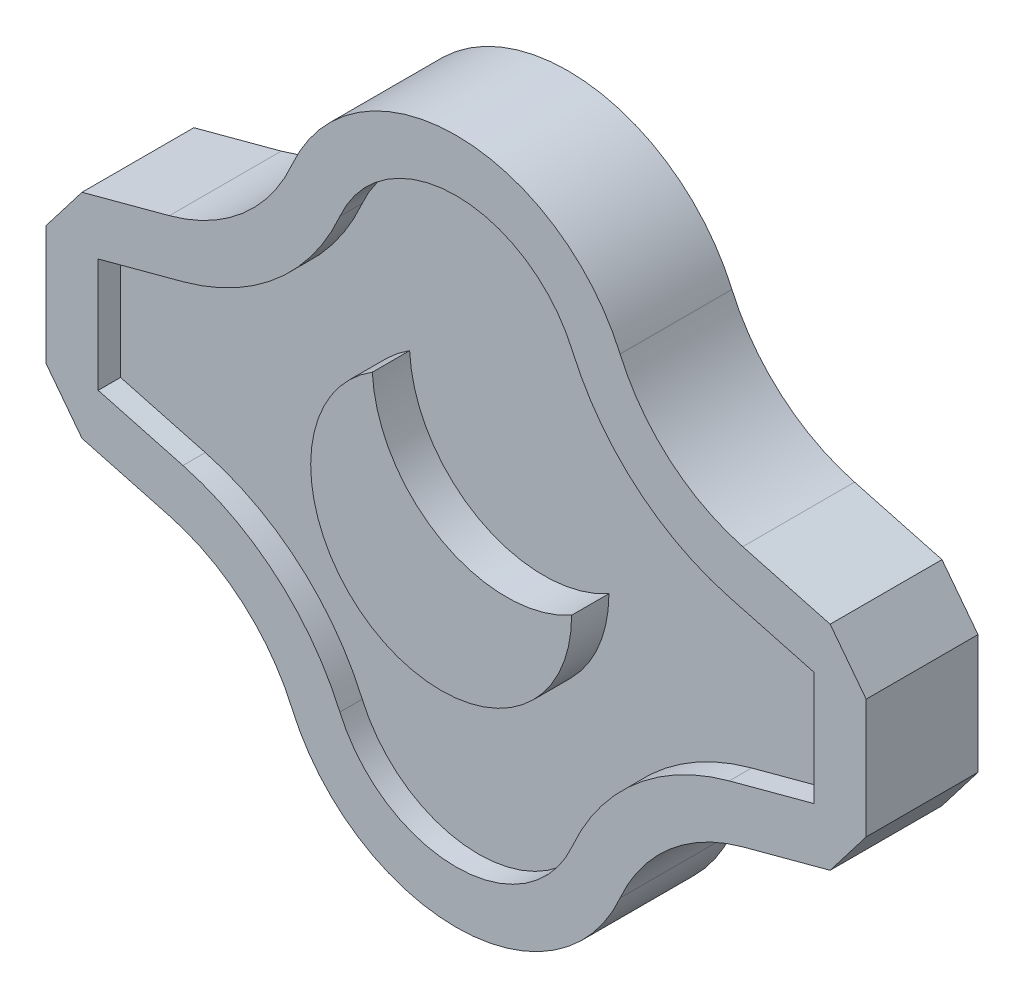
SolidWorks part; units mm, degrees
ref_plane "Front Plane" through (0, 0, 0) normal (0, 0, 1) x (1, 0, 0)
ref_plane "Top Plane" through (0, 0, 0) normal (0, 1, 0) x (1, 0, 0)
ref_plane "Right Plane" through (0, 0, 0) normal (1, 0, 0) x (0, 0, -1)
sketch "Sketch1" plane through (0, 0, 0) normal (0, 0, 1) x (1, 0, 0)
  line L0 (0, 0) -> (-65.8922, 0) construction
  line L1 (0, 0) -> (0, 42.9244) construction
  line L2 (-55, -13) -> (-55, 13)
  line L3 (-55, 13) -> (-38.4458, 17.4357)
  line L4 (-55, 13) -> (-31.6506, 13) construction
  line L5 (0, 46) -> (28.2781, 46) construction
  line L6 (55, -13) -> (55, 13)
  line L7 (55, 13) -> (38.4458, 17.4357)
  line L8 (-55, -13) -> (-38.4458, -17.4357)
  line L9 (55, -13) -> (38.4458, -17.4357)
  arc A0 (-38.4458, 17.4357) -> (-21.9998, 31.5921) centre (-44.9163, 41.5838) ccw
  arc A1 (-21.9998, 31.5921) -> (21.9998, 31.5921) centre (0, 22) cw
  arc A2 (38.4458, 17.4357) -> (21.9998, 31.5921) centre (44.9163, 41.5838) cw
  arc A3 (-38.4458, -17.4357) -> (-21.9998, -31.5921) centre (-44.9163, -41.5838) cw
  arc A4 (-21.9998, -31.5921) -> (21.9998, -31.5921) centre (0, -22) ccw
  arc A5 (38.4458, -17.4357) -> (21.9998, -31.5921) centre (44.9163, -41.5838) ccw
  point P19 (-55, 0)
  point P27 (55, 0)
  dimension "D1" = 55
  dimension "D3" = 24
  dimension "D4" = 25
  dimension "D6" = 22
  dimension "D2" = 13
  dimension "D5" = 15
extrude "Boss-Extrude1" add sketch "Sketch1" along normal blind 15 contours L6 L7 A2 A1 A0 L3 L2 L8 A3 A4 A5 L9
sketch "Sketch2" plane through (0, 0, 15) normal (0, 0, 1) x (1, 0, 0)
  line L12 (36.6341, -10.6742) -> (48, -7.6287)
  line L13 (48, -7.6287) -> (48, 7.6287)
  line L14 (48, 7.6287) -> (36.6341, 10.6742)
  line L15 (-36.6341, 10.6742) -> (-48, 7.6287)
  line L16 (-48, 7.6287) -> (-48, -7.6287)
  line L17 (-48, -7.6287) -> (-36.6341, -10.6742)
  line L18 (36.6341, -10.6742) -> (48, -7.6287)
  line L19 (48, -7.6287) -> (48, 7.6287)
  line L20 (48, 7.6287) -> (36.6341, 10.6742)
  line L21 (-36.6341, 10.6742) -> (-48, 7.6287)
  line L22 (-48, 7.6287) -> (-48, -7.6287)
  line L23 (-48, -7.6287) -> (-36.6341, -10.6742)
  arc A12 (15.5832, 28.7944) -> (36.6341, 10.6742) centre (44.9163, 41.5838) ccw
  arc A13 (15.5832, 28.7944) -> (-15.5832, 28.7944) centre (0, 22) ccw
  arc A14 (-36.6341, 10.6742) -> (-15.5832, 28.7944) centre (-44.9163, 41.5838) ccw
  arc A15 (-15.5832, -28.7944) -> (-36.6341, -10.6742) centre (-44.9163, -41.5838) ccw
  arc A16 (-15.5832, -28.7944) -> (15.5832, -28.7944) centre (0, -22) ccw
  arc A17 (36.6341, -10.6742) -> (15.5832, -28.7944) centre (44.9163, -41.5838) ccw
  arc A18 (15.5832, 28.7944) -> (36.6341, 10.6742) centre (44.9163, 41.5838) ccw
  arc A19 (15.5832, 28.7944) -> (-15.5832, 28.7944) centre (0, 22) ccw
  arc A20 (-36.6341, 10.6742) -> (-15.5832, 28.7944) centre (-44.9163, 41.5838) ccw
  arc A21 (-15.5832, -28.7944) -> (-36.6341, -10.6742) centre (-44.9163, -41.5838) ccw
  arc A22 (-15.5832, -28.7944) -> (15.5832, -28.7944) centre (0, -22) ccw
  arc A23 (36.6341, -10.6742) -> (15.5832, -28.7944) centre (44.9163, -41.5838) ccw
  dimension "D1" = 7
extrude "Cut-Extrude1" cut sketch "Sketch2" against normal blind 3
sketch "Sketch3" plane through (0, 0, 12) normal (0, 0, 1) x (1, 0, 0)
  circle A0 centre (0, 0) radius 17.5
  arc A1 (-9.2294, 14.8684) -> (17.5, 0) centre (8.75, 15.7301) ccw
  point P6 (17.5, 0)
  point P7 (0, 0)
  dimension "D1" = 35
  dimension "D2" = 18
extrude "Boss-Extrude2" add sketch "Sketch3" along normal blind 5 contours A1 A0
sketch "Sketch4" plane through (0, 0, 0) normal (0, 0, -1) x (-1, 0, 0)
  arc A0 (-17.5, 0) -> (9.2294, 14.8684) centre (-8.75, 15.7301) ccw construction
  circle A1 centre (0, 0) radius 17.5
  circle A2 centre (0, 0) radius 17.5
  arc A3 (-17.5, 0) -> (9.2294, 14.8684) centre (-8.75, 15.7301) ccw
  dimension "D1" = 0
extrude "Cut-Extrude2" cut sketch "Sketch4" against normal blind 3 contours A3 A2
chamfer "Chamfer1" distance 5 4 edges at (-55, -13, 7.5) (-55, 13, 7.5) (55, -13, 7.5) (55, 13, 7.5)
